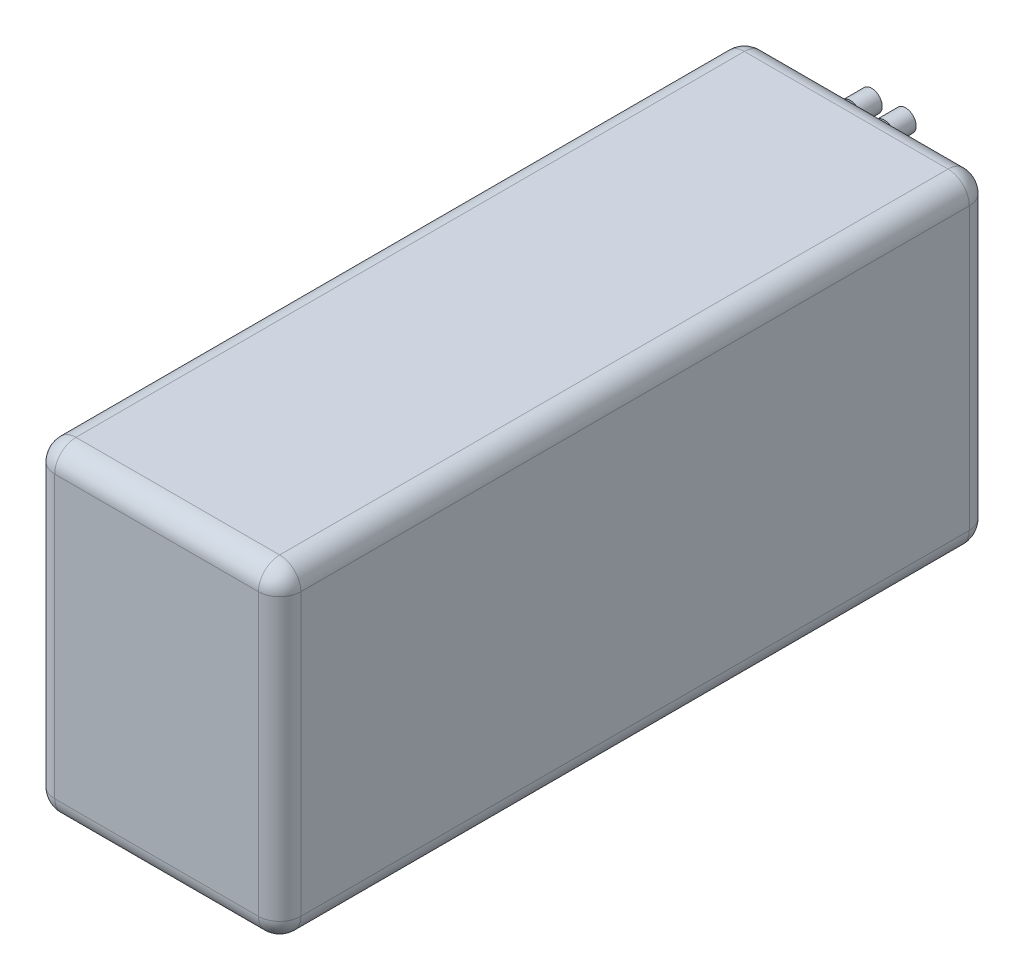
SolidWorks part; units mm, degrees
ref_plane "Спереди" through (0, 0, 0) normal (0, 0, 1) x (1, 0, 0)
ref_plane "Сверху" through (0, 0, 0) normal (0, 1, 0) x (1, 0, 0)
ref_plane "Справа" through (0, 0, 0) normal (1, 0, 0) x (0, 0, -1)
sketch "Эскиз1" plane through (0, 0, 0) normal (0, 1, 0) x (1, 0, 0)
  line L1 (-11.6, 33.5) -> (11.6, 33.5)
  line L2 (-11.6, 33.5) -> (-11.6, -33.5)
  line L3 (-11.6, -33.5) -> (11.6, -33.5)
  line L4 (11.6, 33.5) -> (11.6, -33.5)
  line L5 (-11.6, 33.5) -> (11.6, -33.5) construction
  line L6 (-11.6, -33.5) -> (11.6, 33.5) construction
  point P0 (0, 0)
  dimension "D1" = 23.2
  dimension "D2" = 67
extrude "Бобышка-Вытянуть1" add sketch "Эскиз1" along normal blind 30.5
fillet "Скругление2" radius 2 12 edges at (0, 0, -33.5) (0, 30.5, -33.5) (-11.6, 0, 0) (-11.6, 15.25, -33.5) (-11.6, 30.5, 0) (11.6, 0, 0) (11.6, 30.5, 0) (11.6, 15.25, -33.5) (0, 0, 33.5) (-11.6, 15.25, 33.5) (0, 30.5, 33.5) (11.6, 15.25, 33.5)
sketch "Эскиз2" plane through (0, 0, -33.5) normal (0, 0, -1) x (-1, 0, 0)
  line L0 (-11.6, 28.5) -> (11.6, 28.5) construction
  line L1 (-11.6, 2) -> (-11.6, 28.5) construction
  line L2 (11.6, 28.5) -> (11.6, 2) construction
  line L3 (-9.6, 30.5) -> (9.6, 30.5) construction
  line L4 (-11.6, 4.6983) -> (11.6, 4.6983) construction
  circle A0 centre (-1.6, 28.5) radius 1
  circle A1 centre (1.6, 28.5) radius 1
  circle A2 centre (-0.6, 4.6983) radius 0.5
  circle A3 centre (-2.1, 4.6983) radius 0.5
  circle A4 centre (0.6, 4.6983) radius 0.5
  circle A5 centre (2.1, 4.6983) radius 0.5
  point P8 (-1.6, 28.5)
  point P9 (1.6, 28.5)
  dimension "D4" = 2
  dimension "D5" = 2
  dimension "D8" = 1
  dimension "D9" = 1
  dimension "D10" = 1
  dimension "D11" = 1
  dimension "D1" = 2
  dimension "D2" = 10
  dimension "D3" = 10
  dimension "D6" = 9.5
  dimension "D7" = 11
  dimension "D12" = 11
  dimension "D13" = 9.5
extrude "Бобышка-Вытянуть2" add sketch "Эскиз2" along normal blind 2
